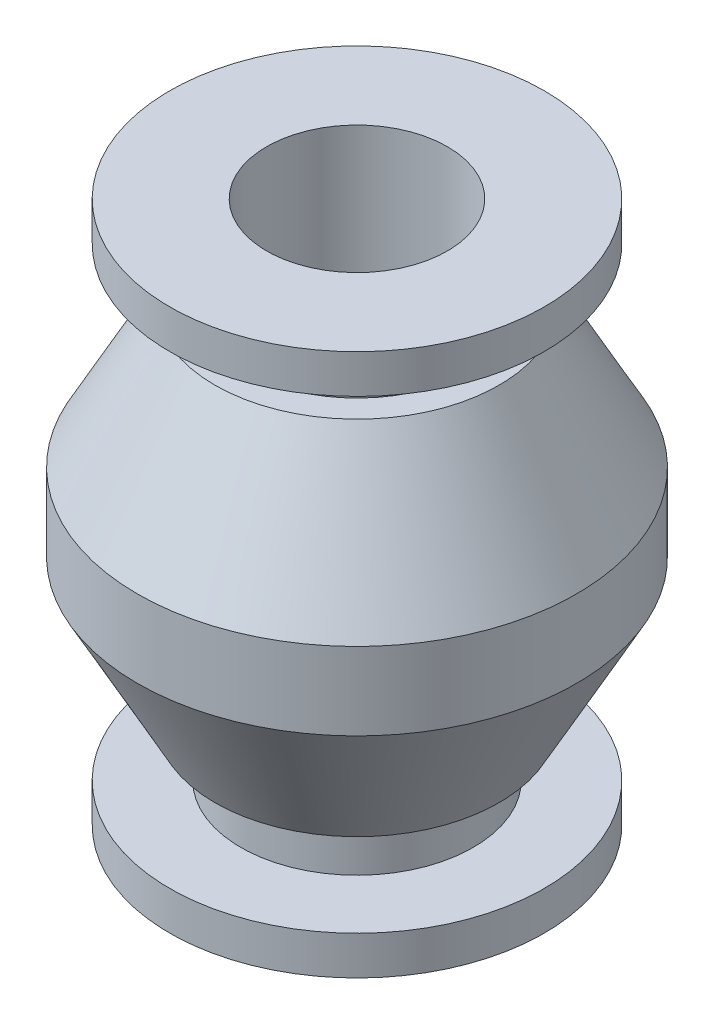
SolidWorks part; units mm, degrees
ref_plane "Alzado" through (0, 0, 0) normal (0, 0, 1) x (1, 0, 0)
ref_plane "Planta" through (0, 0, 0) normal (0, 1, 0) x (1, 0, 0)
ref_plane "Vista lateral" through (0, 0, 0) normal (1, 0, 0) x (0, 0, -1)
sketch "Croquis1" plane through (0, 0, 0) normal (0, 0, 1) x (1, 0, 0)
  line L0 (0, 0) -> (0, 10.5) construction
  line L1 (-3.5, 10.5) -> (-3.5, -10.5)
  line L2 (-3.5, 10.5) -> (-7.25, 10.5)
  line L3 (-7.25, 10.5) -> (-7.25, 9)
  line L4 (-7.25, 9) -> (-4.5, 9)
  line L5 (-4.5, 9) -> (-4.5, 7)
  line L6 (-4.5, 7) -> (-5.5, 7)
  line L7 (-3.5, 0) -> (-8.5, 0) construction
  line L8 (-8.5, -1.5) -> (-8.5, 1.5)
  line L9 (-8.5, 1.5) -> (-5.5, 7)
  line L10 (-8.5, -1.5) -> (-5.5, -7)
  line L11 (-4.5, -7) -> (-5.5, -7)
  line L12 (-4.5, -9) -> (-4.5, -7)
  line L13 (-7.25, -9) -> (-4.5, -9)
  line L14 (-7.25, -10.5) -> (-7.25, -9)
  line L15 (-3.5, -10.5) -> (-7.25, -10.5)
  dimension "D1" = 10.5
  dimension "D2" = 3.5
  dimension "D3" = 7.25
  dimension "D4" = 8.5
  dimension "D5" = 2
  dimension "D6" = 1.5
  dimension "D7" = 1
  dimension "D8" = 4.5
  dimension "D9" = 1.5
revolve "Revolución2" add sketch "Croquis1" angle 360 about L0
